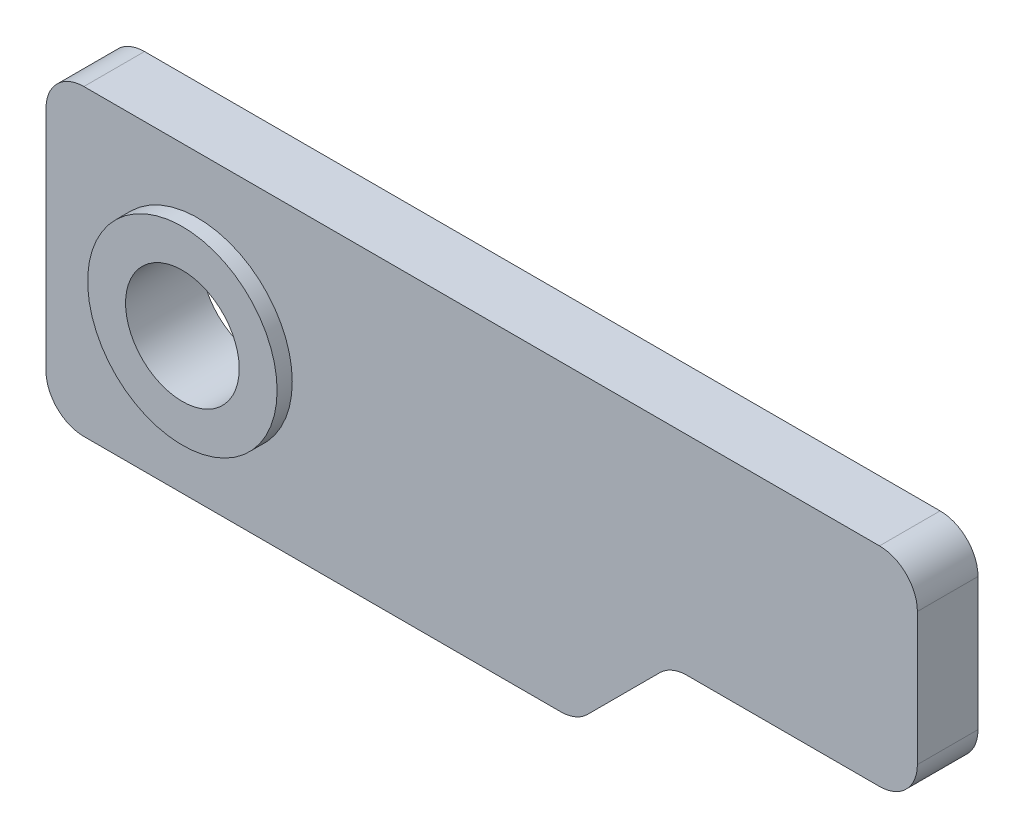
SolidWorks part; units mm, degrees
ref_plane "XY" through (0, 0, 0) normal (0, 0, 1) x (1, 0, 0)
ref_plane "XZ" through (0, 0, 0) normal (0, 1, 0) x (1, 0, 0)
ref_plane "YZ" through (0, 0, 0) normal (1, 0, 0) x (0, 0, -1)
sketch "Sketch1" plane through (0, 0, 0) normal (0, 0, 1) x (1, 0, 0)
  line L0 (11.5, -1.5) -> (5, -1.5)
  line L1 (11.5, -4) -> (2.5, -4) construction
  line L2 (11.5, -4) -> (11.5, -1.5) construction
  line L3 (11.5, 4) -> (-11.5, 4)
  line L4 (-11.5, -4) -> (-11.5, 4)
  line L5 (11.5, -4) -> (-11.5, 4) construction
  line L6 (11.5, 4) -> (-11.5, -4) construction
  line L7 (5, -1.5) -> (2.5, -4)
  line L8 (2.5, -4) -> (-11.5, -4)
  line L9 (11.5, -1.5) -> (11.5, 4)
  circle A0 centre (-7.5, 0) radius 1.5
  point P0 (0, 0)
  dimension "D6" = 7.5
  dimension "D7" = 3
  dimension "D1" = 23
  dimension "D2" = 8
  dimension "D3" = 135
  dimension "D4" = 5.5
  dimension "D5" = 6.5
extrude "Boss-Extrude1" add sketch "Sketch1" along normal blind 2
sketch "Sketch2" plane through (0, 0, 2) normal (0, 0, 1) x (1, 0, 0)
  line L6 (-11.5, 4) -> (-11.5, -4)
  line L7 (-11.5, -4) -> (2.5, -4)
  line L8 (2.5, -4) -> (5, -1.5)
  line L9 (5, -1.5) -> (11.5, -1.5)
  line L10 (11.5, -1.5) -> (11.5, 4)
  line L11 (11.5, 4) -> (-11.5, 4)
  line L12 (-11.5, 4) -> (-11.5, -4)
  line L13 (-11.5, -4) -> (2.5, -4)
  line L14 (2.5, -4) -> (5, -1.5)
  line L15 (5, -1.5) -> (11.5, -1.5)
  line L16 (11.5, -1.5) -> (11.5, 4)
  line L17 (11.5, 4) -> (-11.5, 4)
  circle A2 centre (-7.5, 0) radius 2.5
  circle A3 centre (-7.5, 0) radius 2.5
  dimension "D1" = 0
  dimension "D2" = 1
extrude "Cut-Extrude1" cut sketch "Sketch2" against normal blind 0.4
fillet "Fillet1" radius 1 6 edges at (11.5, -1.5, 0.8) (5, -1.5, 0.8) (2.5, -4, 0.8) (11.5, 4, 0.8) (-11.5, -4, 0.8) (-11.5, 4, 0.8)
